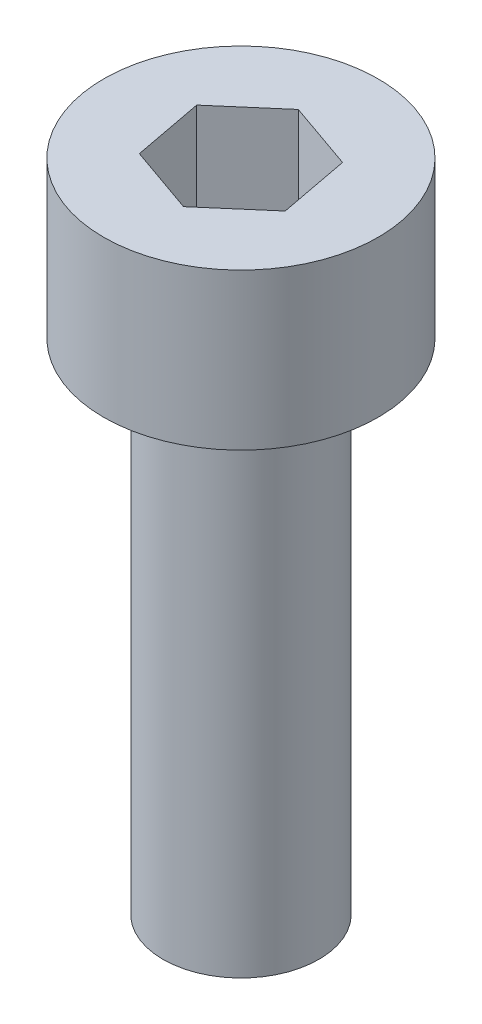
SolidWorks part; units mm, degrees
material "AISI 316L Acero inoxidable"
ref_plane "Alzado" through (0, 0, 0) normal (0, 0, 1) x (1, 0, 0)
ref_plane "Planta" through (0, 0, 0) normal (0, 1, 0) x (1, 0, 0)
ref_plane "Vista lateral" through (0, 0, 0) normal (1, 0, 0) x (0, 0, -1)
sketch "Croquis1" plane through (0, 0, 0) normal (0, 0, 1) x (1, 0, 0)
  line L0 (0, 0) -> (-1.25, 0)
  line L1 (-1.25, 0) -> (-1.25, 8)
  line L2 (-1.25, 8) -> (-2.2, 8)
  line L3 (-2.2, 8) -> (-2.2, 10.5)
  line L4 (-2.2, 10.5) -> (-0.8406, 10.5)
  line L5 (-0.8406, 10.5) -> (-0.8406, 8.8222)
  line L6 (-0.8406, 8.8222) -> (0, 8.8222)
  line L7 (0, 8.8222) -> (0, 0)
  dimension "D1" = 1.25
  dimension "D2" = 8
  dimension "D3" = 2.2
  dimension "D4" = 2.5
revolve "Revolución1" add sketch "Croquis1" angle 360 about L7
sketch "Croquis2" plane through (0, 10.5, 0) normal (0, 1, 0) x (1, 0, 0)
  line L1 (0.875, 0.7534) -> (-0.215, 1.1345)
  line L2 (-0.215, 1.1345) -> (-1.09, 0.3811)
  line L3 (-1.09, 0.3811) -> (-0.875, -0.7534)
  line L4 (-0.875, -0.7534) -> (0.215, -1.1345)
  line L5 (0.215, -1.1345) -> (1.09, -0.3811)
  line L6 (1.09, -0.3811) -> (0.875, 0.7534)
  circle A0 centre (0, 0) radius 1 construction
  dimension "D1" = 2
extrude "Cortar-Extruir1" cut sketch "Croquis2" against normal blind 2
